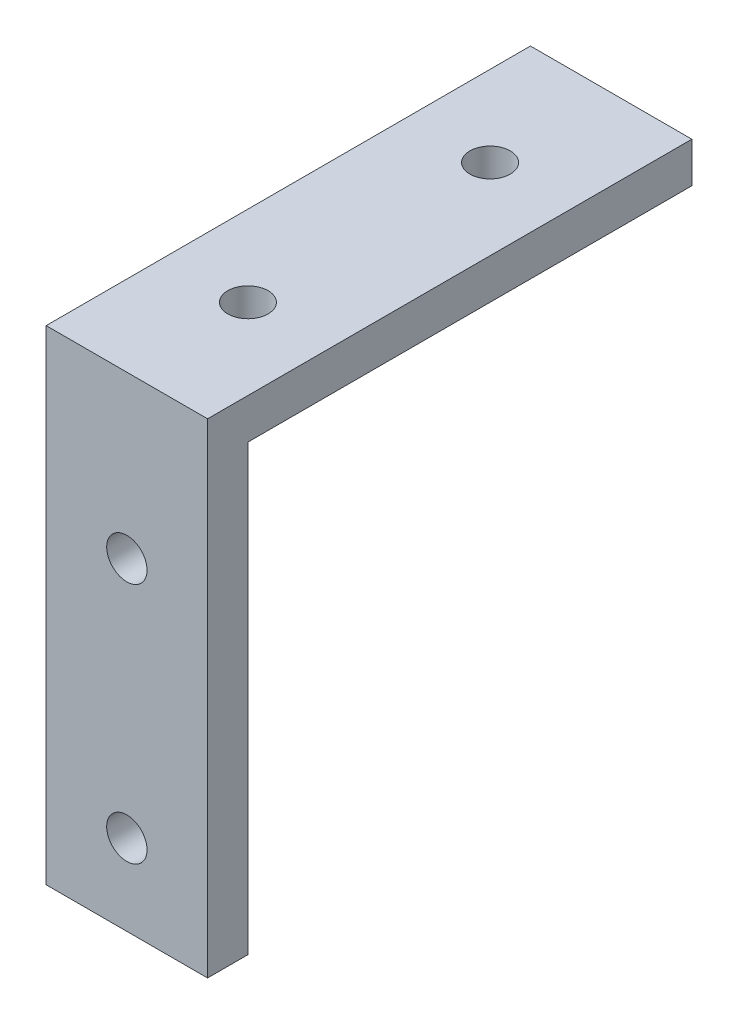
SolidWorks part; units mm, degrees
ref_plane "Front Plane" through (0, 0, 0) normal (0, 0, 1) x (1, 0, 0)
ref_plane "Top Plane" through (0, 0, 0) normal (0, 1, 0) x (1, 0, 0)
ref_plane "Right Plane" through (0, 0, 0) normal (1, 0, 0) x (0, 0, -1)
sketch "Sketch1" plane through (0, 0, 0) normal (1, 0, 0) x (0, 0, -1)
  line L0 (0, 0) -> (0, -69.85)
  line L1 (0, -69.85) -> (-6.35, -69.85)
  line L2 (-6.35, -69.85) -> (-6.35, 6.35)
  line L3 (-6.35, 6.35) -> (69.85, 6.35)
  line L4 (69.85, 6.35) -> (69.85, 0)
  line L5 (69.85, 0) -> (0, 0)
  dimension "D1" = 76.2
  dimension "D2" = 6.35
extrude "Boss-Extrude1" add sketch "Sketch1" along normal mid plane 25.4
sketch "Sketch2" plane through (0, 0, 0) normal (0, 1, 0) x (1, 0, 0)
  line L0 (12.7, 69.85) -> (-12.7, 69.85) construction
  circle A0 centre (0, 50.8) radius 3.175
  circle A1 centre (0, 12.7) radius 3.175
  dimension "D3" = 6.35
  dimension "D1" = 38.1
  dimension "D2" = 19.05
extrude "Cut-Extrude1" cut sketch "Sketch2" along normal through all
sketch "Sketch3" plane through (0, 0, 0) normal (0, 0, 1) x (1, 0, 0)
  circle A0 centre (0, -57.15) radius 3.175
  circle A1 centre (0, -19.05) radius 3.175
  dimension "D3" = 6.35
  dimension "D1" = 38.1
  dimension "D2" = 19.05
extrude "Cut-Extrude2" cut sketch "Sketch3" along normal through all
